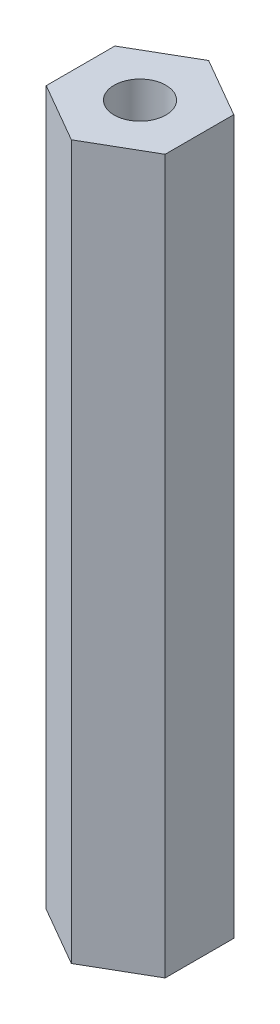
SolidWorks part; units mm, degrees
material "6061-T6 (SS)"
ref_plane "Front Plane" through (0, 0, 0) normal (0, 0, 1) x (1, 0, 0)
ref_plane "Top Plane" through (0, 0, 0) normal (0, 1, 0) x (1, 0, 0)
ref_plane "Right Plane" through (0, 0, 0) normal (1, 0, 0) x (0, 0, -1)
sketch "Sketch1" plane through (0, 0, 0) normal (0, 1, 0) x (1, 0, 0)
  line L1 (0, 4.5827) -> (-3.9688, 2.2914)
  line L2 (-3.9688, 2.2914) -> (-3.9688, -2.2914)
  line L3 (-3.9688, -2.2914) -> (0, -4.5827)
  line L4 (0, -4.5827) -> (3.9687, -2.2914)
  line L5 (3.9687, -2.2914) -> (3.9687, 2.2914)
  line L6 (3.9687, 2.2914) -> (0, 4.5827)
  circle A0 centre (0, 0) radius 3.9688 construction
  dimension "D1" = 7.9375
extrude "Boss-Extrude1" add sketch "Sketch1" along normal blind 47.625
hole_wizard "#8-32 Tapped Hole1" positions "Sketch3" profile "Sketch4" tap size "#8-32" standard "Ansi Inch" end condition through all
sketch "Sketch3" plane through (0, 47.625, 0) normal (0, 1, 0) x (-1, 0, 0)
  point P0 (0, 0)
sketch "Sketch4" plane through (0, 47.625, 0) normal (1, 0, 0) x (0, 0, 1)
  line L0 (0, 0) -> (0, 47.625)
  line L1 (0, 47.625) -> (1.7272, 47.625)
  line L2 (1.7272, 47.625) -> (1.7272, 0)
  line L5 (1.7272, 0) -> (0, 0)
  line L11 (0, -6.35) -> (0, 107.95) construction
  dimension "Thru Tap Drill Dia." = 3.4544
  dimension "Thru Tap Drill Depth" = 47.625
cosmetic thread "Hole Thread1" parameters "D2"=4.1656
